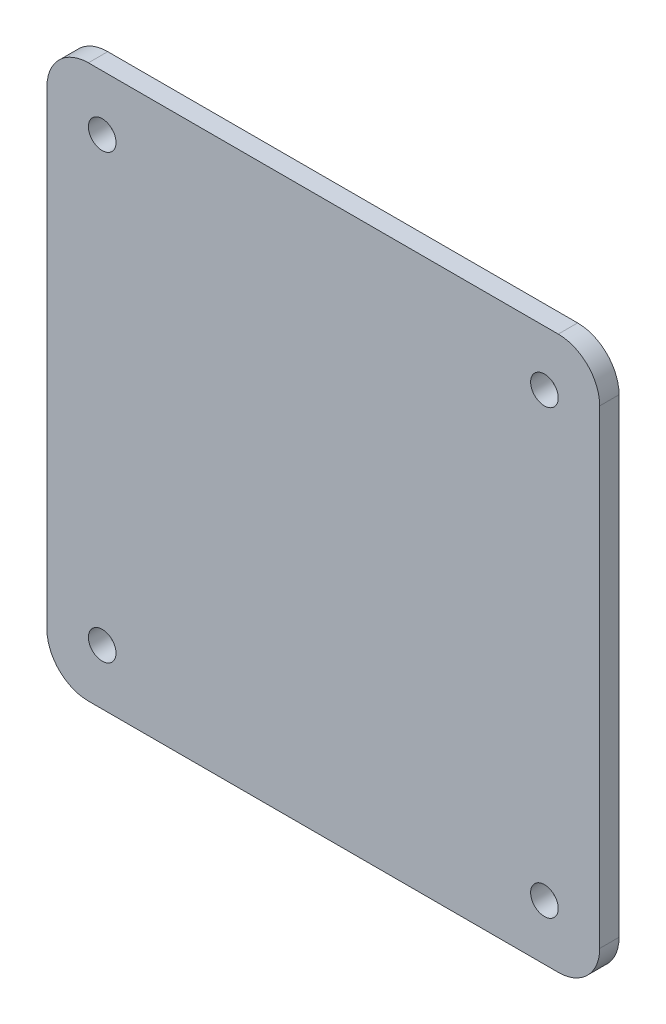
SolidWorks part; units mm, degrees
ref_plane "Plan de face" through (0, 0, 0) normal (0, 0, 1) x (1, 0, 0)
ref_plane "Plan de dessus" through (0, 0, 0) normal (0, 1, 0) x (1, 0, 0)
ref_plane "Plan de droite" through (0, 0, 0) normal (1, 0, 0) x (0, 0, -1)
sketch "Esquisse3" plane through (0, 0, 0) normal (0, 0, 1) x (1, 0, 0)
  line L1 (-100, -100) -> (100, -100)
  line L2 (-100, -100) -> (-100, 100)
  line L3 (-100, 100) -> (100, 100)
  line L4 (100, -100) -> (100, 100)
  line L5 (-80, -80) -> (80, -80) construction
  line L6 (-80, -80) -> (-80, 80) construction
  line L7 (-80, 80) -> (80, 80) construction
  line L8 (80, -80) -> (80, 80) construction
  circle A0 centre (80, 80) radius 5
  circle A1 centre (80, -80) radius 5
  circle A2 centre (-80, -80) radius 5
  circle A3 centre (-80, 80) radius 5
  point P4 (0, 0)
  dimension "D9" = 10
  dimension "D10" = 10
  dimension "D11" = 10
  dimension "D12" = 10
  dimension "D1" = 200
  dimension "D2" = 200
  dimension "D3" = 100
  dimension "D4" = 100
  dimension "D5" = 20
  dimension "D6" = 20
  dimension "D7" = 20
  dimension "D8" = 20
extrude "Boss.-Extru.2" add sketch "Esquisse3" along normal blind 7
fillet "Congé1" radius 15 4 edges at (-100, -100, 3.5) (-100, 100, 3.5) (100, 100, 3.5) (100, -100, 3.5)
sketch "Esquisse4" plane through (0, 0, 7) normal (0, 0, 1) x (1, 0, 0)
  circle A0 centre (0, 0) radius 4.4355
